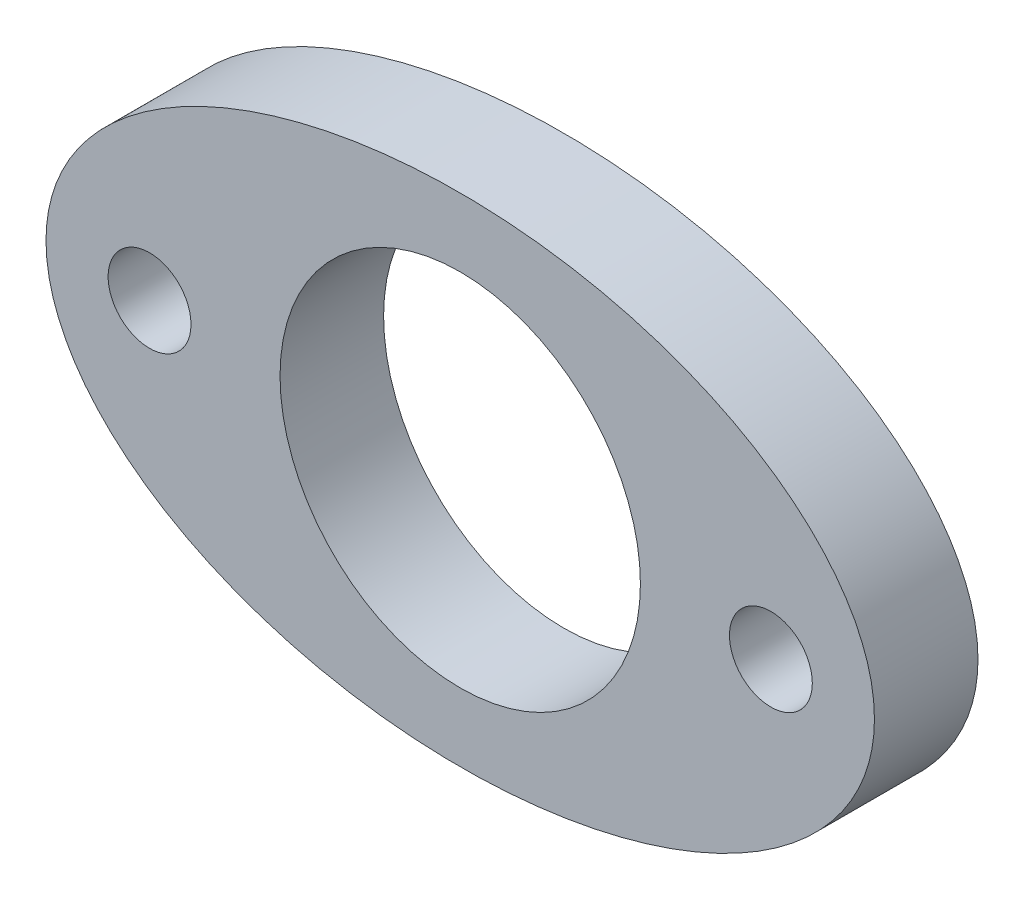
SolidWorks part; units mm, degrees
ref_plane "Front Plane" through (0, 0, 0) normal (0, 0, 1) x (1, 0, 0)
ref_plane "Top Plane" through (0, 0, 0) normal (0, 1, 0) x (1, 0, 0)
ref_plane "Right Plane" through (0, 0, 0) normal (1, 0, 0) x (0, 0, -1)
sketch "Sketch1" plane through (0, 0, 0) normal (0, 0, 1) x (1, 0, 0)
  circle A0 centre (0, 0) radius 11.049
  circle A1 centre (-19.05, 0) radius 2.54
  circle A2 centre (19.05, 0) radius 2.54
  ellipse E0 centre (0, 0) end of major axis (25.4, 0) minor radius 15.24
  dimension "D1" = 22.098
  dimension "D2" = 5.08
  dimension "D4" = 5.08
  dimension "D3" = 19.05
  dimension "D5" = 19.05
  dimension "D6" = 15.24
  dimension "D7" = 25.4
extrude "Boss-Extrude1" add sketch "Sketch1" along normal blind 6.35
